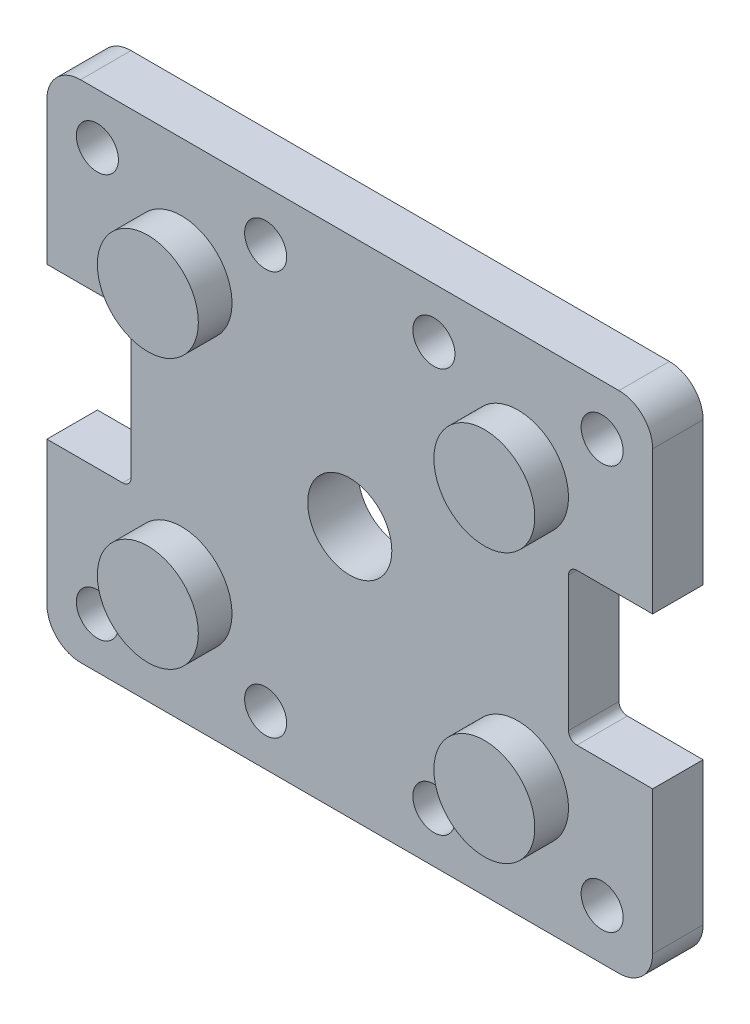
SolidWorks part; units mm, degrees
material "6061-T6 (SS)"
ref_plane "前视基准面" through (0, 0, 0) normal (0, 0, 1) x (1, 0, 0)
ref_plane "上视基准面" through (0, 0, 0) normal (0, 1, 0) x (1, 0, 0)
ref_plane "右视基准面" through (0, 0, 0) normal (1, 0, 0) x (0, 0, -1)
sketch "草图1" plane through (0, 0, 0) normal (0, 0, 1) x (1, 0, 0)
  line L1 (0, 0) -> (36, 0)
  line L2 (0, 0) -> (0, 30)
  line L3 (0, 30) -> (36, 30)
  line L4 (36, 0) -> (36, 30)
  dimension "D1" = 36
  dimension "D2" = 30
extrude "凸台-拉伸1" add sketch "草图1" along normal blind 3
sketch "草图3" plane through (0, 0, 3) normal (0, 0, 1) x (1, 0, 0)
  line L0 (0, 15) -> (36, 15) construction
  line L1 (0, 30) -> (0, 0) construction
  line L2 (36, 0) -> (36, 30) construction
  line L3 (18, 15) -> (18, 24.7823) construction
  line L4 (8, 7) -> (8, 23) construction
  circle A0 centre (8, 23) radius 3
  circle A1 centre (8, 7) radius 3
  circle A2 centre (28, 7) radius 3
  circle A3 centre (28, 23) radius 3
  dimension "D1" = 16
  dimension "D2" = 6
  dimension "D3" = 8
extrude "凸台-拉伸2" add sketch "草图3" along normal blind 2
sketch "草图4" plane through (0, 0, 3) normal (0, 0, 1) x (1, 0, 0)
  line L0 (0, 15) -> (36, 15) construction
  line L1 (0, 30) -> (0, 0) construction
  line L2 (36, 0) -> (36, 30) construction
  line L3 (18, 15) -> (18, 20.9058) construction
  line L4 (31, 10.5) -> (31, 19.5)
  line L5 (5, 10.5) -> (0, 10.5)
  line L6 (5, 10.5) -> (5, 19.5)
  line L7 (5, 19.5) -> (0, 19.5)
  line L8 (0, 10.5) -> (0, 19.5)
  line L9 (5, 10.5) -> (0, 19.5) construction
  line L10 (5, 19.5) -> (0, 10.5) construction
  line L11 (31, 10.5) -> (36, 10.5)
  line L12 (36, 10.5) -> (36, 19.5)
  line L13 (31, 19.5) -> (36, 19.5)
  circle A0 centre (18, 15) radius 2.5 construction
  point P8 (2.5, 15)
  dimension "D3" = 5
  dimension "D1" = 9
  dimension "D2" = 5
extrude "切除-拉伸2" cut sketch "草图4" against normal through all
hole_wizard "M6 螺纹孔1" positions "3D草图2" profile "草图7" tap size "M6" standard "GB" end condition through all
sketch3d "3D草图2"
  point P0 (18, 15, 3)
cosmetic thread "孔螺蚊线1" parameters "D2"=6
sketch "草图7" plane through (18, 15, 3) normal (1, 0, 0) x (0, -1, 0)
  line L0 (0, 0) -> (0, 3)
  line L1 (0, 3) -> (2.5, 3)
  line L2 (2.5, 3) -> (2.5, 0)
  line L5 (2.5, 0) -> (0, 0)
  line L11 (0, -6.35) -> (0, 107.95) construction
  dimension "通孔螺纹孔钻头直径" = 5
  dimension "通孔螺纹孔钻头深度" = 3
fillet "圆角1" radius 0.5 4 edges at (31, 19.5, 1.5) (31, 10.5, 1.5) (5, 10.5, 1.5) (5, 19.5, 1.5)
sketch "草图9" plane through (0, 0, 3) normal (0, 0, 1) x (1, 0, 0)
  line L0 (18, 15) -> (8, 15) construction
  line L1 (0, 10.5) -> (0, 0) construction
  line L2 (3, 27) -> (13, 27) construction
  line L3 (3, 27) -> (3, 3) construction
  line L4 (3, 3) -> (13, 3) construction
  line L5 (13, 27) -> (13, 3) construction
  line L6 (3, 27) -> (13, 3) construction
  line L7 (3, 3) -> (13, 27) construction
  line L8 (0, 0) -> (36, 0) construction
  line L9 (18, 15) -> (18, 25.1751) construction
  circle A0 centre (3, 27) radius 1.5
  circle A1 centre (3, 3) radius 1.5
  circle A2 centre (13, 3) radius 1.5
  circle A3 centre (13, 27) radius 1.5
  circle A4 centre (23, 3) radius 1.5
  circle A5 centre (33, 3) radius 1.5
  circle A6 centre (33, 27) radius 1.5
  circle A7 centre (23, 27) radius 1.5
  dimension "D1" = 3
  dimension "D3" = 3
  dimension "D2" = 3
  dimension "D4" = 10
hole_wizard "大小mm 暗销孔1" positions "3D草图3" profile "草图10" hole size "Ø2.5" standard "GB" end condition through all
sketch3d "3D草图3"
  point P0 (3, 27, 3)
  point P3 (13, 27, 3)
  point P6 (23, 27, 3)
  point P9 (33, 27, 3)
  point P12 (33, 3, 3)
  point P15 (23, 3, 3)
  point P18 (13, 3, 3)
  point P21 (3, 3, 3)
sketch "草图10" plane through (3, 27, 3) normal (1, 0, 0) x (0, -1, 0)
  line L0 (0, 0) -> (0, 3)
  line L1 (0, 3) -> (1.25, 3)
  line L2 (1.25, 3) -> (1.25, 0)
  line L5 (1.25, 0) -> (0, 0)
  line L11 (0, -6.35) -> (0, 107.95) construction
  dimension "通孔孔直径" = 2.5
  dimension "通孔孔深度" = 3
fillet "圆角2" radius 2 4 edges at (36, 0, 1.5) (0, 0, 1.5) (0, 30, 1.5) (36, 30, 1.5)
